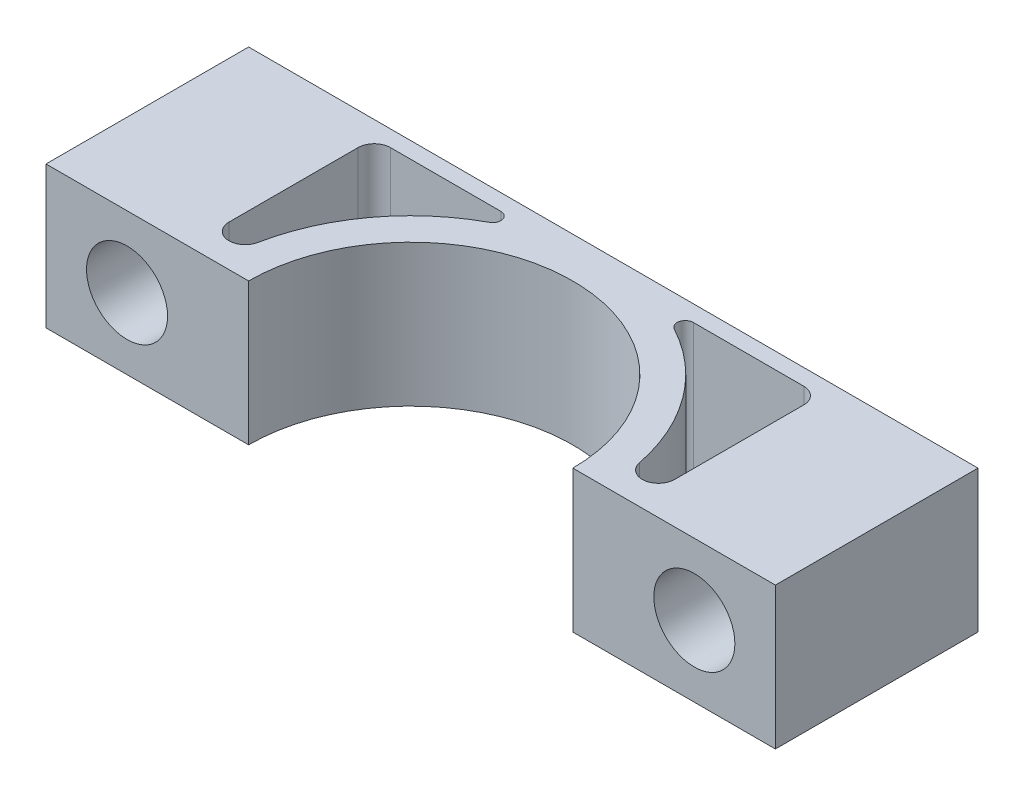
SolidWorks part; units mm, degrees
material "6061-T6 (SS)"
ref_plane "X-Y Datum" through (0, 0, 0) normal (0, 0, 1) x (1, 0, 0)
ref_plane "X-Z Datum" through (0, 0, 0) normal (0, 1, 0) x (1, 0, 0)
ref_plane "Y-Z Datum" through (0, 0, 0) normal (1, 0, 0) x (0, 0, -1)
sketch "Sketch1" plane through (0, 0, 0) normal (0, 1, 0) x (1, 0, 0)
  line L0 (-12.7, 0) -> (-28.575, 0)
  line L1 (-28.575, 0) -> (-28.575, 15.875)
  line L2 (-28.575, 15.875) -> (28.575, 15.875)
  line L3 (28.575, 15.875) -> (28.575, 0)
  line L4 (28.575, 0) -> (12.7, 0)
  line L5 (0, -55) -> (0, 55) construction
  line L6 (16.1925, 14.605) -> (7.5402, 14.605)
  line L7 (-17.4625, 3.2223) -> (-17.4625, 13.335)
  line L8 (-16.1925, 14.605) -> (-7.5402, 14.605)
  line L9 (17.4625, 3.2223) -> (17.4625, 13.335)
  arc A0 (-12.7, 0) -> (12.7, 0) centre (0, 0) cw
  arc A1 (-14.9469, 2.9744) -> (-7.2386, 13.4112) centre (0, 0) cw
  arc A2 (-17.4625, 3.2223) -> (-14.9469, 2.9744) centre (-16.1925, 3.2223) ccw
  arc A3 (16.1925, 14.605) -> (17.4625, 13.335) centre (16.1925, 13.335) cw
  arc A4 (7.2386, 13.4112) -> (7.5402, 14.605) centre (7.5402, 13.97) cw
  arc A5 (-15.24, 0) -> (15.24, 0) centre (0, 0) cw construction
  arc A6 (-16.1925, 14.605) -> (-17.4625, 13.335) centre (-16.1925, 13.335) ccw
  arc A7 (-7.2386, 13.4112) -> (-7.5402, 14.605) centre (-7.5402, 13.97) ccw
  arc A8 (14.9469, 2.9744) -> (7.2386, 13.4112) centre (0, 0) ccw
  arc A9 (17.4625, 3.2223) -> (14.9469, 2.9744) centre (16.1925, 3.2223) cw
  dimension "D1" = 15.875
  dimension "D2" = 12.7
  dimension "D8" = 1.27
  dimension "D10" = 0.635
  dimension "D4" = 1.27
  dimension "D3" = 57.15
  dimension "D5" = 11.1125
  dimension "D7" = 1.27
  dimension "D6" = 2.54
extrude "Boss-Extrude1" add sketch "Sketch1" along normal mid plane 11.1252
sketch "Sketch2" plane through (0, 0, 0) normal (0, 0, 1) x (1, 0, 0)
  line L0 (-22.225, 0) -> (22.225, 0) construction
  circle A0 centre (-22.225, 0) radius 3.175
  circle A1 centre (22.225, 0) radius 3.175
  point P4 (0, 0)
  dimension "D1" = 6.35
  dimension "D2" = 22.225
extrude "Cut-Extrude1" cut sketch "Sketch2" against normal through all
fillet "Fillet1" [suppressed] radius 3.81
fillet "Fillet2" [suppressed] radius 0.254
